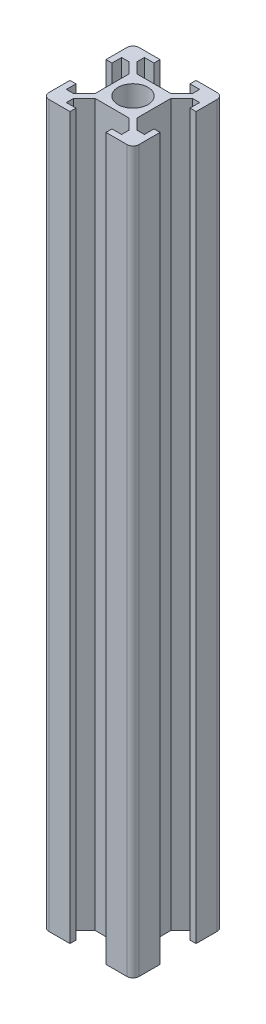
SolidWorks part; units mm, degrees
ref_plane "Front Plane" through (0, 0, 0) normal (0, 0, 1) x (1, 0, 0)
ref_plane "Top Plane" through (0, 0, 0) normal (0, 1, 0) x (1, 0, 0)
ref_plane "Right Plane" through (0, 0, 0) normal (1, 0, 0) x (0, 0, -1)
sketch "Sketch1" plane through (0, 0, 0) normal (0, 1, 0) x (1, 0, 0)
  line L0 (-7.5, -3) -> (-7.5, -6.5)
  line L5 (-6.5, -7.5) -> (-3, -7.5)
  line L6 (-7.5, -3) -> (-6.5, -3)
  line L7 (-3, -7.5) -> (-3, -6.5)
  line L8 (-6.5, -3) -> (-6.5, -4.6)
  line L9 (-3, -6.5) -> (-4.6, -6.5)
  line L10 (-6.5, -4.6) -> (-5.3071, -4.6)
  line L11 (-4.6, -6.5) -> (-4.6, -5.3071)
  line L13 (-3.5071, 0) -> (-3.5071, -2.8)
  line L14 (-3.5071, -2.8) -> (-5.3071, -4.6)
  line L16 (0, -3.5071) -> (-2.8, -3.5071)
  line L17 (-2.8, -3.5071) -> (-4.6, -5.3071)
  line L18 (-3.5071, 2.8) -> (-5.3071, 4.6)
  line L19 (-6.5, 4.6) -> (-5.3071, 4.6)
  line L20 (-6.5, 3) -> (-6.5, 4.6)
  line L21 (-7.5, 3) -> (-6.5, 3)
  line L22 (-7.5, 6.5) -> (-7.5, 3)
  line L23 (-3, 7.5) -> (-6.5, 7.5)
  line L24 (-3, 7.5) -> (-3, 6.5)
  line L25 (-3, 6.5) -> (-4.6, 6.5)
  line L26 (-4.6, 6.5) -> (-4.6, 5.3071)
  line L27 (-2.8, 3.5071) -> (-4.6, 5.3071)
  line L28 (0, 3.5071) -> (-2.8, 3.5071)
  line L31 (-3.5071, 0) -> (-3.5071, 2.8)
  line L32 (2.8, 3.5071) -> (4.6, 5.3071)
  line L33 (4.6, 6.5) -> (4.6, 5.3071)
  line L34 (3, 6.5) -> (4.6, 6.5)
  line L35 (3, 7.5) -> (3, 6.5)
  line L36 (6.5, 7.5) -> (3, 7.5)
  line L37 (7.5, 3) -> (7.5, 6.5)
  line L38 (7.5, 3) -> (6.5, 3)
  line L39 (6.5, 3) -> (6.5, 4.6)
  line L40 (6.5, 4.6) -> (5.3071, 4.6)
  line L41 (3.5071, 2.8) -> (5.3071, 4.6)
  line L42 (3.5071, 0) -> (3.5071, 2.8)
  line L45 (0, 3.5071) -> (2.8, 3.5071)
  line L46 (3.5071, -2.8) -> (5.3071, -4.6)
  line L47 (6.5, -4.6) -> (5.3071, -4.6)
  line L48 (6.5, -3) -> (6.5, -4.6)
  line L49 (7.5, -3) -> (6.5, -3)
  line L50 (7.5, -6.5) -> (7.5, -3)
  line L51 (3, -7.5) -> (6.5, -7.5)
  line L52 (3, -7.5) -> (3, -6.5)
  line L53 (3, -6.5) -> (4.6, -6.5)
  line L54 (4.6, -6.5) -> (4.6, -5.3071)
  line L55 (2.8, -3.5071) -> (4.6, -5.3071)
  line L56 (0, -3.5071) -> (2.8, -3.5071)
  line L59 (3.5071, 0) -> (3.5071, -2.8)
  arc A1 (-6.5, -7.5) -> (-7.5, -6.5) centre (-6.5, -6.5) cw
  arc A2 (-2.5, 0) -> (0, -2.5) centre (0, 0) ccw
  arc A3 (-7.5, 6.5) -> (-6.5, 7.5) centre (-6.5, 6.5) cw
  arc A4 (0, 2.5) -> (-2.5, 0) centre (0, 0) ccw
  arc A5 (6.5, 7.5) -> (7.5, 6.5) centre (6.5, 6.5) cw
  arc A6 (2.5, 0) -> (0, 2.5) centre (0, 0) ccw
  arc A7 (7.5, -6.5) -> (6.5, -7.5) centre (6.5, -6.5) cw
  arc A8 (0, -2.5) -> (2.5, 0) centre (0, 0) ccw
  point P8 (-7.5, -3)
  point P9 (-3, -7.5)
  point P75 (0, 0)
  dimension "D1" = 1
  dimension "D9" = 2.5
  dimension "D2" = 3
  dimension "D3" = 7.5
  dimension "D4" = 3
  dimension "D5" = 1
  dimension "D6" = 1
  dimension "D7" = 1.6
  dimension "D8" = 2.8
  dimension "D10" = 1
  dimension "D11" = 4
extrude "Boss-Extrude1" add sketch "Sketch1" along normal blind 120
